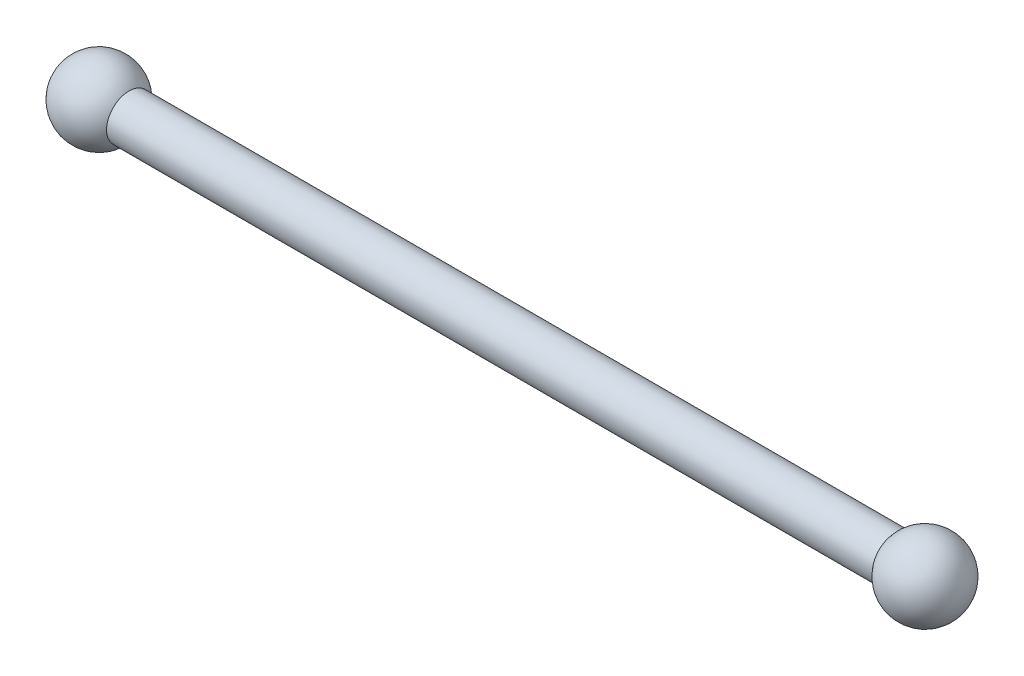
SolidWorks part; units mm, degrees
ref_plane "Front Plane" through (0, 0, 0) normal (0, 0, 1) x (1, 0, 0)
ref_plane "Top Plane" through (0, 0, 0) normal (0, 1, 0) x (1, 0, 0)
ref_plane "Right Plane" through (0, 0, 0) normal (1, 0, 0) x (0, 0, -1)
sketch "Sketch4" plane through (0, 0, 0) normal (1, 0, 0) x (0, 0, -1)
  line L0 (0, 0) -> (2.5, 0)
  line L1 (2.5, 0) -> (2.5, -2.5)
  arc A0 (0, 0) -> (2.5, -2.5) centre (2.5, 0) ccw
  dimension "D3" = 2.5
  dimension "D1" = 2.5
  dimension "D2" = 2.5
revolve "Semi-circle Revolve" add sketch "Sketch4" angle 360 about L1
mirror "Full-circle Mirror" about plane through (0, 0, 0) normal (0, -1, 0) of "Semi-circle Revolve"
sketch "Sketch5" plane through (0, 0, 0) normal (1, 0, 0) x (0, 0, -1)
  line L0 (0, 0) -> (2.5, 0) construction
  circle A0 centre (2.5, 0) radius 1.5
  dimension "D2" = 3
  dimension "D1" = 2.5
extrude "Shaft" add sketch "Sketch5" along normal blind 55
sketch "Sketch6" plane through (55, 0, 0) normal (1, 0, 0) x (0, 0, -1)
  line L0 (0, 0) -> (2.5, 0)
  line L1 (2.5, 0) -> (2.5, -2.5)
  arc A0 (0, 0) -> (2.5, -2.5) centre (2.5, 0) ccw
  dimension "D1" = 2.5
  dimension "D2" = 2.5
revolve "Opposite Semi-circle Revolve" add sketch "Sketch6" angle 360 about L1
mirror "Opposite Full-circle Mirror" about plane through (55, 0, 0) normal (0, 1, 0) of "Opposite Semi-circle Revolve"
